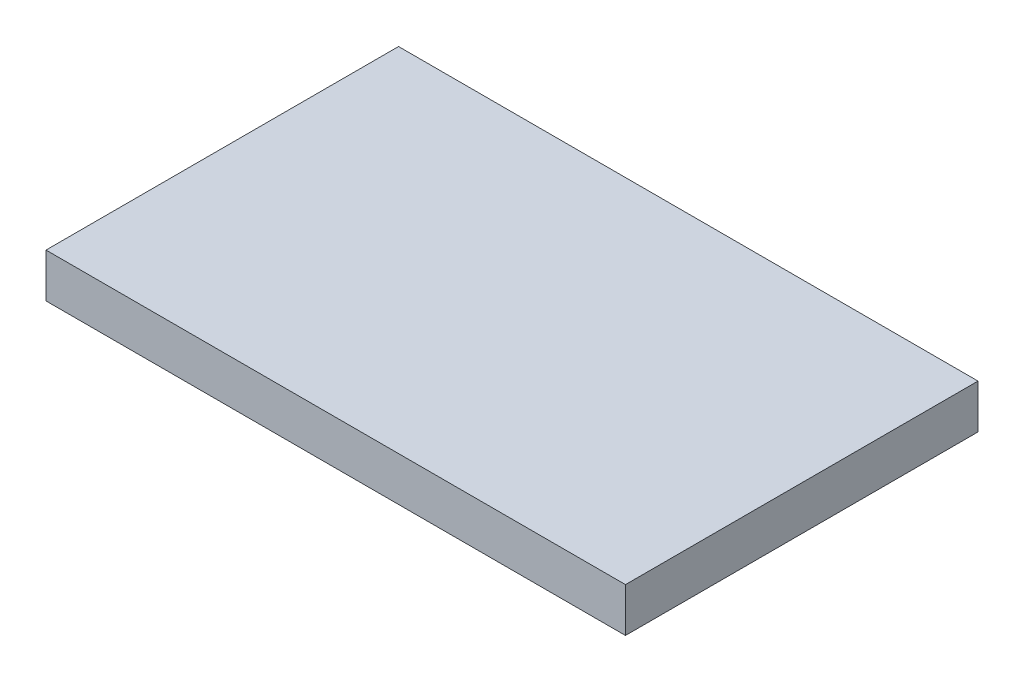
SolidWorks part; units mm, degrees
ref_plane "Front Plane" through (0, 0, 0) normal (0, 0, 1) x (1, 0, 0)
ref_plane "Top Plane" through (0, 0, 0) normal (0, 1, 0) x (1, 0, 0)
ref_plane "Right Plane" through (0, 0, 0) normal (1, 0, 0) x (0, 0, -1)
sketch "Sketch1" plane through (0, 0, 0) normal (0, 1, 0) x (1, 0, 0)
  line B0 (83.5, 50.8) -> (0, 50.8)
  line B1 (0, 50.8) -> (0, 0)
  line B2 (0, 0) -> (83.5, 0)
  line B3 (83.5, 0) -> (83.5, 50.8)
sketch_block_instance "Back-1"
sketch_block "Back"
extrude "Boss-Extrude1" add sketch "Sketch1" along normal blind 6.35
